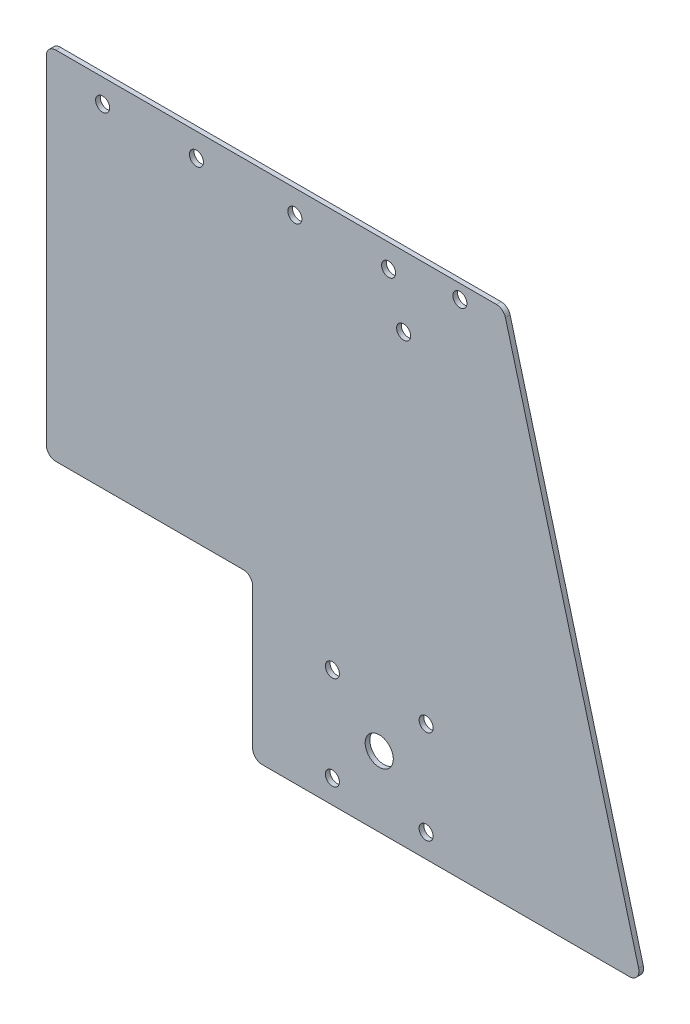
SolidWorks part; units mm, degrees
ref_plane "前视基准面" through (0, 0, 0) normal (0, 0, 1) x (1, 0, 0)
ref_plane "上视基准面" through (0, 0, 0) normal (0, 1, 0) x (1, 0, 0)
ref_plane "右视基准面" through (0, 0, 0) normal (1, 0, 0) x (0, 0, -1)
other "Configuration Table"
sketch "草图1" plane through (0, 0, 0) normal (0, 0, 1) x (1, 0, 0)
  line L0 (0, 0) -> (175, 0)
  line L1 (175, 0) -> (145.5256, 110)
  line L2 (145.5256, 110) -> (0, 110)
  line L3 (0, 110) -> (0, 0)
  line L5 (109, 5) -> (129, 5) construction
  line L6 (109, 5) -> (109, 25) construction
  line L7 (109, 25) -> (129, 25) construction
  line L8 (129, 5) -> (129, 25) construction
  line L9 (109, 5) -> (129, 25) construction
  line L10 (109, 25) -> (129, 5) construction
  circle A0 centre (129, 25) radius 1.5
  circle A1 centre (129, 5) radius 1.5
  circle A2 centre (119, 15) radius 3
  circle A3 centre (109, 5) radius 1.5
  circle A4 centre (109, 25) radius 1.5
  point P3 (119, 15)
  dimension "D1" = 3
  dimension "D2" = 6
  dimension "D3" = 20
  dimension "D4" = 15
  dimension "D5" = 75
  dimension "D6" = 109
  dimension "D7" = 175
  dimension "D8" = 110
extrude "凸台-拉伸1" add sketch "草图1" along normal blind 1
sketch "草图4" plane through (0, 0, 0) normal (0, 0, -1) x (-1, 0, 0)
  line L0 (-22, 40) -> (-22, 60) construction
  line L1 (-22, 101) -> (-22, 81) construction
  line L2 (0, 110) -> (0, 0) construction
  line L4 (0, 0) -> (-175, 0) construction
  circle A0 centre (-22, 101) radius 1.5
  circle A1 centre (-22, 81) radius 1.5
  circle A2 centre (-22, 60) radius 1.5
  circle A3 centre (-22, 40) radius 1.5
  dimension "D2" = 22
  dimension "D3" = 3
  dimension "D4" = 40
  dimension "D5" = 21
  dimension "D1" = 20
extrude "切除-拉伸2" cut sketch "草图4" against normal blind 4
sketch "草图5" plane through (0, 0, 0) normal (0, 0, -1) x (-1, 0, 0)
  line L0 (-136.2, 107) -> (-124.2, 95) construction
  line L2 (0, 110) -> (0, 0) construction
  line L3 (0, 0) -> (-175, 0) construction
  circle A0 centre (-136.2, 107) radius 1.5
  circle A1 centre (-124.2, 95) radius 1.5
  dimension "D3" = 3
  dimension "D4" = 95
  dimension "D5" = 136.2
  dimension "D1" = 12
  dimension "D2" = 12
extrude "切除-拉伸3" cut sketch "草图5" against normal blind 10
sketch "草图6" plane through (0, 0, 1) normal (0, 0, 1) x (1, 0, 0)
  line L1 (0, 0) -> (53, 0)
  line L2 (0, 0) -> (0, 34)
  line L3 (0, 34) -> (53, 34)
  line L4 (53, 0) -> (53, 34)
  dimension "D1" = 34
  dimension "D2" = 53
extrude "切除-拉伸4" cut sketch "草图6" against normal blind 10
sketch "草图7" plane through (0, 0, 1) normal (0, 0, 1) x (1, 0, 0)
  line L1 (53, 0) -> (92, 0)
  line L2 (53, 0) -> (53, 34)
  line L3 (53, 34) -> (92, 34)
  line L4 (92, 0) -> (92, 34)
  dimension "D1" = 39
  dimension "D2" = 34
extrude "切除-拉伸5" cut sketch "草图7" against normal blind 10
sketch "草图8" [suppressed] plane through (0, 0, 1) normal (0, 0, 1) x (1, 0, 0)
  line L1 (70, 81) -> (115, 81) construction
  line L2 (70, 81) -> (70, 62.5) construction
  line L3 (70, 62.5) -> (115, 62.5) construction
  line L4 (115, 81) -> (115, 62.5) construction
  line L5 (90, 34) -> (0, 34) construction
  line L6 (92.5, 81) -> (92.5, 62.5) construction
  line L7 (0, 120) -> (0, 34) construction
  circle A0 centre (115, 81) radius 1.5
  circle A1 centre (115, 62.5) radius 1.5
  circle A2 centre (70, 62.5) radius 1.5
  circle A3 centre (70, 81) radius 1.5
  dimension "D3" = 3
  dimension "D1" = 18.5
  dimension "D2" = 45
  dimension "D4" = 92.5
  dimension "D5" = 28.5
extrude "切除-拉伸6" [suppressed] cut sketch "草图8" against normal blind 10
sketch "草图9" [suppressed] plane through (0, 0, 1) normal (0, 0, 1) x (1, 0, 0)
  line L0 (92.5, 84.5) -> (92.5, 62.5) construction
  line L1 (70, 84.5) -> (115, 84.5) construction
  line L2 (70, 84.5) -> (70, 62.5) construction
  line L3 (70, 62.5) -> (115, 62.5) construction
  line L4 (115, 84.5) -> (115, 62.5) construction
  line L5 (0, 120) -> (0, 34) construction
  line L6 (92, 34) -> (0, 34) construction
  circle A0 centre (115, 84.5) radius 1.5
  circle A1 centre (115, 62.5) radius 1.5
  circle A2 centre (70, 62.5) radius 1.5
  circle A3 centre (70, 84.5) radius 1.5
  dimension "D5" = 3
  dimension "D1" = 92.5
  dimension "D2" = 28.5
  dimension "D3" = 45
  dimension "D4" = 22
extrude "切除-拉伸7" [suppressed] cut sketch "草图9" against normal blind 10
sketch "草图10" plane through (0, 0, 1) normal (0, 0, 1) x (1, 0, 0)
  line L0 (145.5256, 110) -> (0, 110) construction
  circle A0 centre (37, 94) radius 10
  circle A1 centre (22, 101) radius 1.5 construction
  dimension "D1" = 20
  dimension "D2" = 16
  dimension "D3" = 15
extrude "切除-拉伸8" cut sketch "草图10" against normal blind 10
sketch "草图11" [suppressed] plane through (0, 0, 1) normal (0, 0, 1) x (1, 0, 0)
  circle A0 centre (22, 40) radius 1.5 construction
  circle A1 centre (22, 60) radius 1.5 construction
  circle A2 centre (22, 81) radius 1.5 construction
  circle A3 centre (22, 101) radius 1.5 construction
  circle A4 centre (22, 40) radius 1.5
  circle A5 centre (22, 60) radius 1.5
  circle A6 centre (22, 81) radius 1.5
  circle A7 centre (22, 101) radius 1.5
extrude "凸台-拉伸2" [suppressed] add sketch "草图11" against normal blind 1
sketch "草图12" [suppressed] plane through (0, 0, 1) normal (0, 0, 1) x (1, 0, 0)
  line L0 (3, 74) -> (3, 54) construction
  line L2 (0, 120) -> (0, 34) construction
  line L3 (92, 34) -> (0, 34) construction
  circle A0 centre (3, 74) radius 1.5
  circle A1 centre (3, 54) radius 1.5
  dimension "D1" = 3
  dimension "D3" = 20
  dimension "D2" = 20
  dimension "D4" = 3
extrude "切除-拉伸9" [suppressed] cut sketch "草图12" against normal blind 1
sketch "草图13" plane through (0, 0, 1) normal (0, 0, 1) x (1, 0, 0)
  line L0 (101, 105) -> (121, 105) construction
  line L1 (145.5256, 110) -> (0, 110) construction
  line L2 (60, 105) -> (80, 105) construction
  line L3 (0, 110) -> (0, 34) construction
  circle A0 centre (121, 105) radius 1.5
  circle A1 centre (101, 105) radius 1.5
  circle A2 centre (80, 105) radius 1.5
  circle A3 centre (60, 105) radius 1.5
  circle A4 centre (45, 105) radius 1.5
  circle A5 centre (25, 105) radius 1.5
  dimension "D3" = 3
  dimension "D4" = 21
  dimension "D5" = 60
  dimension "D6" = 15
  dimension "D7" = 20
  dimension "D1" = 5
  dimension "D2" = 20
extrude "切除-拉伸10" cut sketch "草图13" against normal blind 1
fillet "圆角1" radius 2 6 edges at (0, 34, 0.5) (145.5256, 110, 0.5) (175, 0, 0.5) (92, 0, 0.5) (92, 34, 0.5) (0, 110, 0.5)
sketch "草图15" [suppressed] plane through (0, 0, 0) normal (0, 0, -1) x (-1, 0, 0)
  line L0 (-142.8461, 120) -> (0, 120) construction
  line L1 (-113.75, 120) -> (-71.25, 120)
  line L2 (-113.75, 120) -> (-113.75, 98.5)
  line L3 (-113.75, 98.5) -> (-71.25, 98.5)
  line L4 (-71.25, 120) -> (-71.25, 98.5)
  line L5 (0, 120) -> (0, 34) construction
  dimension "D1" = 71.25
  dimension "D2" = 42.5
  dimension "D3" = 21.5
extrude "切除-拉伸11" [suppressed] cut sketch "草图15" against normal blind 10
sketch "草图16" [suppressed] plane through (0, 0, 0) normal (0, 0, -1) x (-1, 0, 0)
  line L0 (-60, 115) -> (-30, 115) construction
  circle A0 centre (-30, 115) radius 1.5 construction
  circle A1 centre (-60, 115) radius 1.5 construction
  circle A2 centre (-10, 115) radius 1.5
  circle A3 centre (-50, 115) radius 1.5 construction
  dimension "D2" = 20
  dimension "D3" = 20
  dimension "D1" = 30
extrude "切除-拉伸12" [suppressed] cut sketch "草图16" against normal blind 10
fillet "圆角2" [suppressed] radius 2
fillet "圆角3" [suppressed] radius 2
sketch "草图17" [suppressed] plane through (0, 0, 1) normal (0, 0, 1) x (1, 0, 0)
  line L0 (141.3114, 120) -> (2, 120) construction
  line L1 (71.25, 120) -> (113.75, 120)
  line L2 (71.25, 120) -> (71.25, 113.5)
  line L3 (71.25, 113.5) -> (113.75, 113.5)
  line L4 (113.75, 120) -> (113.75, 113.5)
  line L5 (0, 118) -> (0, 36) construction
  line L6 (100, 107) -> (85, 107) construction
  line L7 (92.5, 107) -> (92.5, 113.5) construction
  circle A0 centre (85, 107) radius 1.75
  circle A1 centre (100, 107) radius 1.75
  dimension "D4" = 3.5
  dimension "D1" = 71.25
  dimension "D2" = 113.75
  dimension "D3" = 6.5
  dimension "D5" = 13
  dimension "D6" = 15
extrude "切除-拉伸13" [suppressed] cut sketch "草图17" against normal blind 10
sketch "草图18" [suppressed] plane through (0, 0, 1) normal (0, 0, 1) x (1, 0, 0)
  line L0 (71.25, 109.25) -> (113.75, 109.25) construction
  line L1 (71.25, 118) -> (71.25, 100.5) construction
  line L2 (113.75, 100.5) -> (113.75, 118) construction
  line L3 (92.5, 109.25) -> (92.5, 90.5) construction
  line L4 (92.5, 90.5) -> (92.5, 79.5) construction
  line L5 (73.25, 98.5) -> (111.75, 98.5) construction
  circle A0 centre (92.5, 90.5) radius 1.5
  circle A1 centre (92.5, 79.5) radius 1.5
  dimension "D2" = 3
  dimension "D3" = 8
  dimension "D1" = 11
extrude "切除-拉伸14" [suppressed] cut sketch "草图18" against normal blind 10
fillet "圆角4" [suppressed] radius 2
sketch "草图19" [suppressed] plane through (0, 0, 0) normal (0, 0, -1) x (-1, 0, 0)
  line L0 (-3, 54) -> (-3, 74) construction
  line L1 (-3, 74) -> (-10, 74) construction
  line L2 (-10, 74) -> (-10, 54) construction
  line L3 (-10, 54) -> (-3, 54) construction
  circle A0 centre (-10, 74) radius 1.5
  circle A1 centre (-10, 54) radius 1.5
  circle A2 centre (-3, 74) radius 1.5 construction
  dimension "D1" = 7
extrude "切除-拉伸15" [suppressed] cut sketch "草图19" against normal blind 10
sketch "草图20" plane through (0, 0, 0) normal (0, 0, -1) x (-1, 0, 0)
  circle A0 centre (-37, 94) radius 10 construction
  circle A1 centre (-37, 94) radius 10
extrude "凸台-拉伸3" add sketch "草图20" against normal blind 1
sketch "草图21" plane through (0, 0, 0) normal (0, 0, -1) x (-1, 0, 0)
  line L1 (-48, 120) -> (0, 120)
  line L2 (-48, 120) -> (-48, 34)
  line L3 (-48, 34) -> (0, 34)
  line L4 (0, 120) -> (0, 34)
  line L5 (-90, 34) -> (-2, 34) construction
  line L6 (0, 108) -> (0, 36) construction
  dimension "D1" = 48
  dimension "D2" = 86
extrude "切除-拉伸16" cut sketch "草图21" against normal blind 10
fillet "圆角5" radius 2 2 edges at (48, 34, 0.5) (48, 110, 0.5)
sketch "草图22" [suppressed] plane through (0, 0, 0) normal (0, 0, -1) x (-1, 0, 0)
  line L0 (-115.75, 120) -> (-69.25, 120)
  line L10 (-90, 34) -> (-50, 34)
  line L11 (-48, 36) -> (-48, 118)
  line L12 (-50, 120) -> (-69.25, 120)
  line L13 (-71.25, 118) -> (-71.25, 100.5)
  line L14 (-73.25, 98.5) -> (-111.75, 98.5)
  line L15 (-113.75, 100.5) -> (-113.75, 118)
  line L16 (-115.75, 120) -> (-141.3114, 120)
  line L17 (-143.2433, 118.5176) -> (-174.3254, 2.5176)
  line L18 (-172.3935, 0) -> (-94, 0)
  line L19 (-92, 2) -> (-92, 32)
  line L20 (-90, 34) -> (-50, 34)
  line L21 (-48, 36) -> (-48, 118)
  line L22 (-50, 120) -> (-69.25, 120)
  line L23 (-71.25, 118) -> (-71.25, 100.5)
  line L24 (-73.25, 98.5) -> (-111.75, 98.5)
  line L25 (-113.75, 100.5) -> (-113.75, 118)
  line L26 (-115.75, 120) -> (-141.3114, 120)
  line L27 (-143.2433, 118.5176) -> (-174.3254, 2.5176)
  line L28 (-172.3935, 0) -> (-94, 0)
  line L29 (-92, 2) -> (-92, 32)
  arc A10 (-50, 34) -> (-48, 36) centre (-50, 36) ccw
  arc A11 (-48, 118) -> (-50, 120) centre (-50, 118) ccw
  arc A12 (-69.25, 120) -> (-71.25, 118) centre (-69.25, 118) ccw
  arc A13 (-73.25, 98.5) -> (-71.25, 100.5) centre (-73.25, 100.5) ccw
  arc A14 (-113.75, 100.5) -> (-111.75, 98.5) centre (-111.75, 100.5) ccw
  arc A15 (-113.75, 118) -> (-115.75, 120) centre (-115.75, 118) ccw
  arc A16 (-141.3114, 120) -> (-143.2433, 118.5176) centre (-141.3114, 118) ccw
  arc A17 (-174.3254, 2.5176) -> (-172.3935, 0) centre (-172.3935, 2) ccw
  arc A18 (-94, 0) -> (-92, 2) centre (-94, 2) ccw
  arc A19 (-90, 34) -> (-92, 32) centre (-90, 32) ccw
  arc A20 (-50, 34) -> (-48, 36) centre (-50, 36) ccw
  arc A21 (-48, 118) -> (-50, 120) centre (-50, 118) ccw
  arc A22 (-69.25, 120) -> (-71.25, 118) centre (-69.25, 118) ccw
  arc A23 (-73.25, 98.5) -> (-71.25, 100.5) centre (-73.25, 100.5) ccw
  arc A24 (-113.75, 100.5) -> (-111.75, 98.5) centre (-111.75, 100.5) ccw
  arc A25 (-113.75, 118) -> (-115.75, 120) centre (-115.75, 118) ccw
  arc A26 (-141.3114, 120) -> (-143.2433, 118.5176) centre (-141.3114, 118) ccw
  arc A27 (-174.3254, 2.5176) -> (-172.3935, 0) centre (-172.3935, 2) ccw
  arc A28 (-94, 0) -> (-92, 2) centre (-94, 2) ccw
  arc A29 (-90, 34) -> (-92, 32) centre (-90, 32) ccw
  arc M36 (-69.25, 120) -> (-71.25, 118) centre (-69.25, 118) ccw
  line M37 (-71.25, 118) -> (-71.25, 100.5)
  arc M38 (-71.25, 100.5) -> (-73.25, 98.5) centre (-73.25, 100.5) cw
  line M39 (-73.25, 98.5) -> (-111.75, 98.5)
  arc M40 (-111.75, 98.5) -> (-113.75, 100.5) centre (-111.75, 100.5) cw
  line M41 (-113.75, 100.5) -> (-113.75, 118)
  arc M42 (-113.75, 118) -> (-115.75, 120) centre (-115.75, 118) ccw
  dimension "D1" = 0
extrude "凸台-拉伸4" [suppressed] add sketch "草图22" against normal blind 1 contours L0 M42 M41 M40 M39 M38 M37 M36
sketch "草图23" [suppressed] plane through (0, 0, 0) normal (0, 0, -1) x (-1, 0, 0)
  line L0 (-121, 115) -> (-60, 115) construction
  circle A0 centre (-80, 115) radius 1.5
  circle A1 centre (-101, 115) radius 1.5
  circle A2 centre (-121, 115) radius 1.5 construction
  circle A3 centre (-60, 115) radius 1.5 construction
  dimension "D1" = 20
  dimension "D2" = 20
extrude "切除-拉伸17" [suppressed] cut sketch "草图23" against normal blind 1
